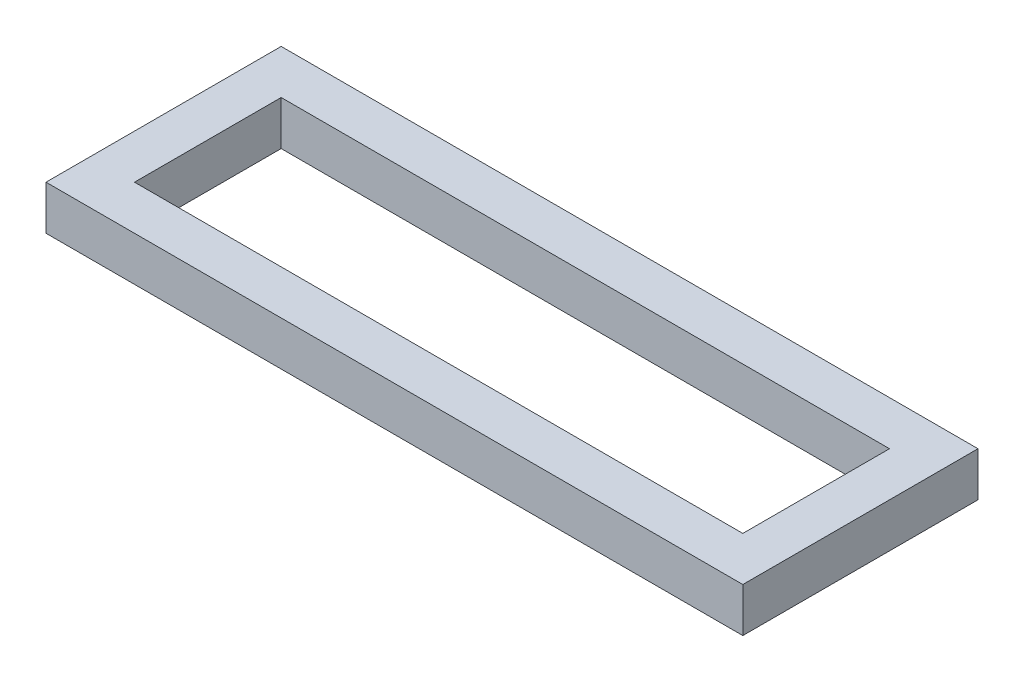
SolidWorks part; units mm, degrees
ref_plane "Front Plane" through (0, 0, 0) normal (0, 0, 1) x (1, 0, 0)
ref_plane "Top Plane" through (0, 0, 0) normal (0, 1, 0) x (1, 0, 0)
ref_plane "Right Plane" through (0, 0, 0) normal (1, 0, 0) x (0, 0, -1)
sketch "Sketch1" plane through (0, 0, 0) normal (0, 1, 0) x (1, 0, 0)
  line L1 (-200, -67.5) -> (200, -67.5)
  line L2 (-200, -67.5) -> (-200, 67.5)
  line L3 (-200, 67.5) -> (200, 67.5)
  line L4 (200, -67.5) -> (200, 67.5)
  line L5 (-200, -67.5) -> (200, 67.5) construction
  line L6 (-200, 67.5) -> (200, -67.5) construction
  line L7 (-174.6, -42.1) -> (174.6, -42.1)
  line L8 (-174.6, -42.1) -> (-174.6, 42.1)
  line L9 (-174.6, 42.1) -> (174.6, 42.1)
  line L10 (174.6, -42.1) -> (174.6, 42.1)
  line L11 (-174.6, -42.1) -> (174.6, 42.1) construction
  line L12 (-174.6, 42.1) -> (174.6, -42.1) construction
  point P0 (0, 0)
  point P6 (0, 0)
  dimension "D1" = 400
  dimension "D2" = 349.2
  dimension "D3" = 135
  dimension "D4" = 84.2
extrude "Boss-Extrude1" add sketch "Sketch1" along normal blind 25.4
